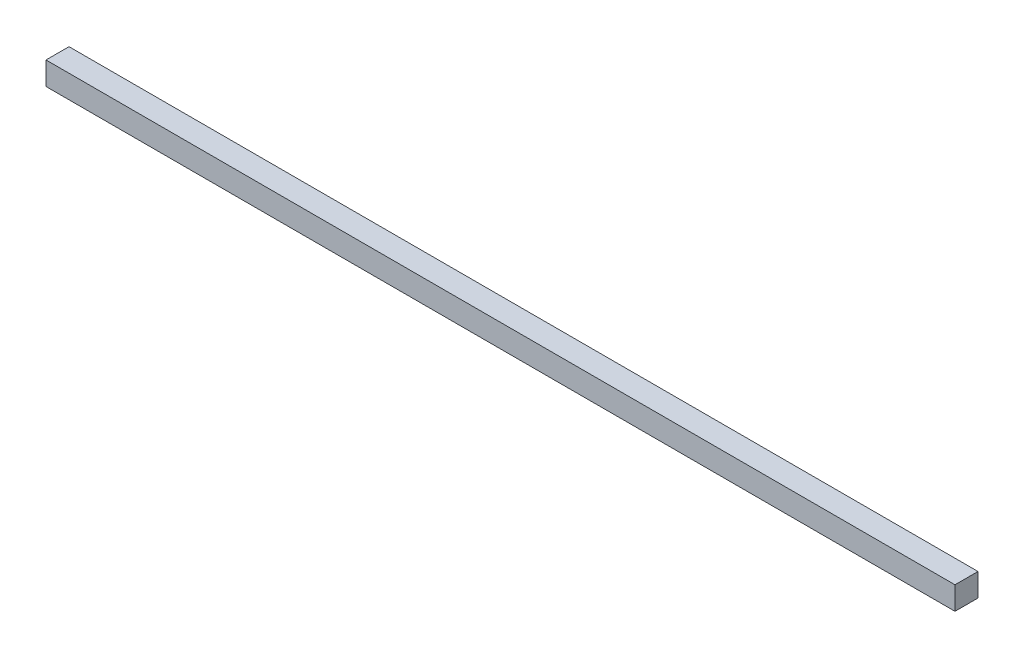
SolidWorks part; units mm, degrees
ref_plane "Front Plane" through (0, 0, 0) normal (0, 0, 1) x (1, 0, 0)
ref_plane "Top Plane" through (0, 0, 0) normal (0, 1, 0) x (1, 0, 0)
ref_plane "Right Plane" through (0, 0, 0) normal (1, 0, 0) x (0, 0, -1)
other "Configuration Table"
sketch "Sketch1" plane through (0, 0, 0) normal (0, 0, 1) x (1, 0, 0)
  line L1 (0, 0) -> (250.825, 0)
  line L2 (0, 0) -> (0, 6.35)
  line L3 (0, 6.35) -> (250.825, 6.35)
  line L4 (250.825, 0) -> (250.825, 6.35)
  dimension "D1" = 6.35
  dimension "D2" = 250.825
extrude "Extrude1" add sketch "Sketch1" along normal blind 6.35
